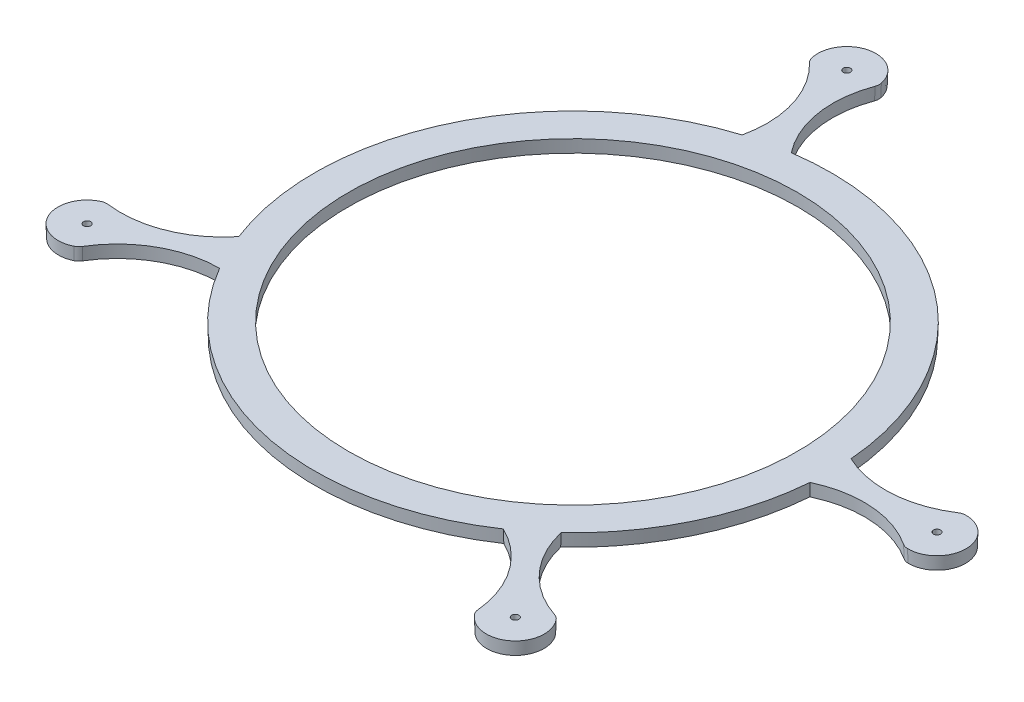
SolidWorks part; units mm, degrees
ref_plane "Front Plane" through (0, 0, 0) normal (0, 0, 1) x (1, 0, 0)
ref_plane "Top Plane" through (0, 0, 0) normal (0, 1, 0) x (1, 0, 0)
ref_plane "Right Plane" through (0, 0, 0) normal (1, 0, 0) x (0, 0, -1)
sketch "Sketch1" plane through (0, 0, 0) normal (0, 1, 0) x (1, 0, 0)
  circle A0 centre (0, 0) radius 63.5
  circle A1 centre (0, 0) radius 55.372
  dimension "D1" = 127
  dimension "D2" = 110.744
extrude "Boss-Extrude1" add sketch "Sketch1" along normal blind 3.175
sketch "Sketch2" plane through (0, 0, 0) normal (0, 1, 0) x (1, 0, 0)
  line L0 (0, 0) -> (143.528, 0) construction
  line L1 (0, 0) -> (63.3043, -4.9822) construction
  line L4 (87.0973, 5.9593) -> (88.1774, 6.6273) construction
  line L85 (89.3678, -7.0334) -> (106.3854, -8.3727) construction
  arc A0 (89.5346, -7.041) -> (89.5346, 7.041) centre (89.6247, 0) ccw
  arc A1 (63.3043, -4.9822) -> (88.1774, -6.6273) centre (74.2802, -27.8883) cw
  arc A2 (88.1774, 6.6273) -> (89.5346, 7.041) centre (89.5671, 4.5012) cw
  circle A3 centre (0, 0) radius 63.5 construction
  arc A4 (88.1774, -6.6273) -> (89.5346, -7.041) centre (89.5671, -4.5012) ccw
  arc A5 (63.3043, -4.9822) -> (63.3043, 4.9822) centre (0, 0) ccw
  arc A6 (63.3043, 4.9822) -> (88.1774, 6.6273) centre (74.2802, 27.8883) ccw
  point P13 (88.7043, -6.9812)
  point P84 (74.2802, 27.8883)
  dimension "D1" = 25.4
  dimension "D2" = 25.4
  dimension "D3" = 2.54
  dimension "D4" = 4.5
extrude "Boss-Extrude2" add sketch "Sketch2" along normal blind 3.175 contours A5 A6 A2 A0 A4 A1
sketch "Sketch37" plane through (0, 3.175, 0) normal (0, 1, 0) x (1, 0, 0)
  line L0 (89.6247, 0) -> (0, 0) construction
  circle A0 centre (89.6247, 0) radius 0.889
  dimension "D1" = 1.778
extrude "Cut-Extrude19" cut sketch "Sketch37" against normal through all
draft "Draft20" type of draft neutral plane draft angle 2 faces to draft 2 face at (0, 3.175, 55.372) face at (-0.0979, 1.5875, 0) neutral plane through (0, 0, 0) neutral plane normal (0, -1, 0) parameters "D1"=2
draft "Draft21" type of draft neutral plane draft angle 2 faces to draft 5 face at (88.8413, 1.5875, 6.8825) face at (75.8935, 1.9844, 4.1615) face at (88.8413, 1.5875, -6.8825) face at (93.1005, 1.5875, 0) face at (75.8935, 1.9844, -4.1615) neutral plane through (0, 0, 0) neutral plane normal (0, -1, 0) parameters "D1"=2
pattern_circular "CirPattern7" count 7 over 360 about axis through (0, 0, 0) along (0, 1, 0) of "Boss-Extrude2", "Cut-Extrude19", "Draft21"
